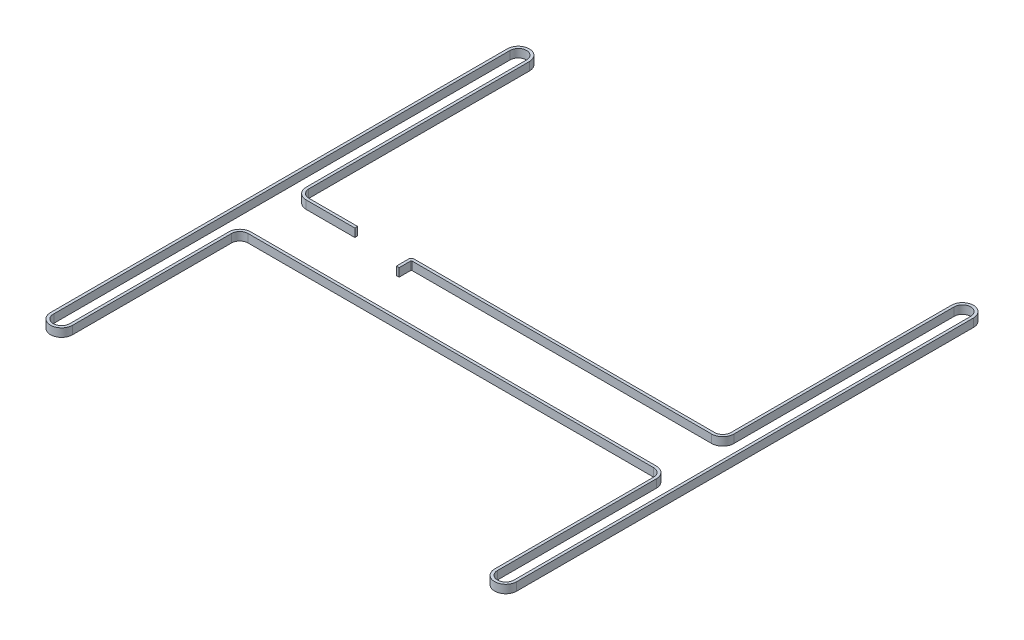
SolidWorks part; units mm, degrees
ref_plane "Front Plane" through (0, 0, 0) normal (0, 0, 1) x (1, 0, 0)
ref_plane "Top Plane" through (0, 0, 0) normal (0, 1, 0) x (1, 0, 0)
ref_plane "Right Plane" through (0, 0, 0) normal (1, 0, 0) x (0, 0, -1)
sketch "Sketch1" plane through (0, 0, 0) normal (0, 1, 0) x (1, 0, 0)
  line L19 (7.9882, 331.5013) -> (7.9882, 171.3375)
  line L20 (13.9843, 165.5534) -> (49.3079, 165.5534)
  line L21 (-8.0118, 331.5013) -> (-8.025, 0.0006)
  line L26 (7.975, 0) -> (7.975, 115.3567)
  line L27 (13.975, 121.3567) -> (308.3372, 121.3544)
  line L29 (314.3372, 0.0002) -> (314.3372, 115.3544)
  line L30 (330.3372, 0.0002) -> (330.3372, 331.5)
  line L31 (314.3374, 171.5523) -> (314.3374, 331.6932)
  line L32 (308.3374, 165.5523) -> (90.293, 165.5523)
  line L33 (5.975, 0) -> (5.975, 115.3567)
  line L34 (-5.9987, 0.5614) -> (-5.9987, 331.5013)
  line L35 (5.975, 331.5013) -> (5.9744, 171.5535)
  line L36 (13.9843, 163.5435) -> (49.3079, 163.5435)
  line L37 (49.3079, 163.5435) -> (49.3079, 165.5534)
  line L38 (308.3372, 123.3544) -> (13.7817, 123.3544)
  line L39 (316.3372, 115.3544) -> (316.3372, 0.0002)
  line L40 (328.3372, 0.0002) -> (328.3367, 331.5)
  line L41 (316.3375, 331.3513) -> (316.3375, 171.5523)
  line L42 (308.3374, 163.5522) -> (90.7932, 163.5522)
  line L46 (88.293, 157.4246) -> (88.293, 163.5522)
  line L48 (90.2932, 157.4246) -> (90.2932, 163.0522)
  line L50 (88.293, 157.4246) -> (88.293, 154.6579)
  line L51 (88.293, 154.6579) -> (90.2932, 154.6579)
  line L52 (90.2932, 157.4246) -> (90.2932, 154.6579)
  line L53 (88.293, 163.5522) -> (88.293, 163.5523)
  arc A18 (7.9882, 331.5013) -> (-8.0118, 331.5013) centre (-0.0118, 331.5013) ccw
  arc A19 (7.9882, 171.3375) -> (13.9843, 165.5534) centre (13.9843, 171.5534) ccw
  arc A20 (-8.025, 0.0006) -> (7.975, 0) centre (-0.025, 0) ccw
  arc A23 (314.3372, 0.0002) -> (330.3372, 0.0002) centre (322.3372, 0.0002) ccw
  arc A24 (316.3372, 0.0002) -> (328.3372, 0.0002) centre (322.3372, 0.0002) ccw
  arc A25 (330.3372, 331.5) -> (314.3374, 331.6932) centre (322.3362, 331.5) ccw
  arc A27 (308.3374, 165.5523) -> (314.3374, 171.5523) centre (308.3374, 171.5523) ccw
  arc A28 (314.3372, 115.3544) -> (308.3372, 121.3544) centre (308.3372, 115.3544) ccw
  arc A30 (316.3372, 115.3544) -> (308.3372, 123.3544) centre (308.3372, 115.3544) ccw
  arc A31 (13.975, 121.3567) -> (7.975, 115.3567) centre (13.975, 115.3567) ccw
  arc A32 (13.7817, 123.3544) -> (5.975, 115.3567) centre (13.975, 115.3567) ccw
  arc A33 (-5.9987, 0.5614) -> (5.975, 0) centre (-0.025, 0) ccw
  arc A35 (5.975, 331.5013) -> (-5.9987, 331.5013) centre (-0.0118, 331.5013) ccw
  arc A36 (5.9744, 171.5535) -> (13.9843, 163.5435) centre (13.9843, 171.5534) ccw
  arc A37 (308.3374, 163.5522) -> (316.3375, 171.5523) centre (308.3374, 171.5523) ccw
  arc A38 (328.3367, 331.5) -> (316.3375, 331.3513) centre (322.3362, 331.5) ccw
  arc A39 (88.293, 163.5523) -> (90.293, 165.5523) centre (90.293, 163.5523) cw
  arc A40 (90.7932, 163.5522) -> (90.2932, 163.0522) centre (90.7932, 163.0522) ccw
  dimension "D1" = 2
  dimension "D6" = 16
  dimension "D2" = 16
  dimension "D3" = 16
  dimension "D4" = 16
  dimension "D5" = 12
  dimension "D7" = 12
  dimension "D8" = 0.5
extrude "Boss-Extrude2" add sketch "Sketch1" along normal blind 6
